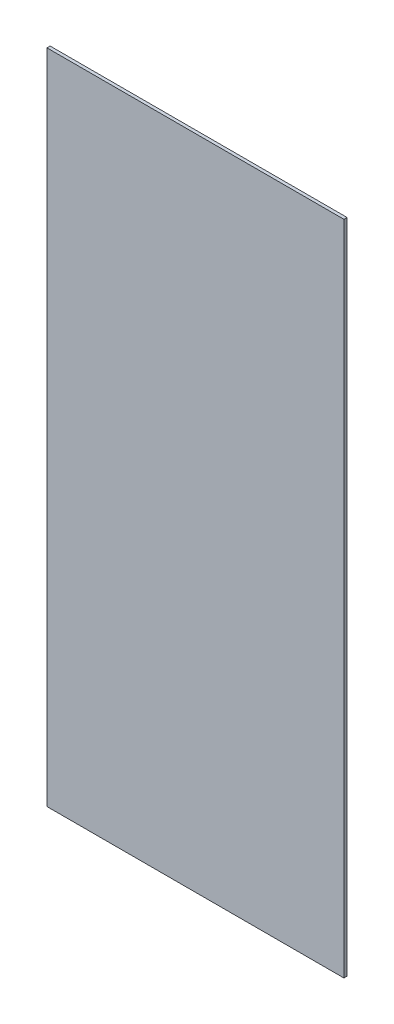
SolidWorks part; units mm, degrees
material "Vidro"
ref_plane "Plano frontal" through (0, 0, 0) normal (0, 0, 1) x (1, 0, 0)
ref_plane "Plano superior" through (0, 0, 0) normal (0, 1, 0) x (1, 0, 0)
ref_plane "Plano direito" through (0, 0, 0) normal (1, 0, 0) x (0, 0, -1)
sketch "Esboço1" plane through (0, 0, 0) normal (0, 0, 1) x (1, 0, 0)
  line L1 (-47, -104) -> (47, -104)
  line L2 (-47, -104) -> (-47, 104)
  line L3 (-47, 104) -> (47, 104)
  line L4 (47, -104) -> (47, 104)
  line L5 (-47, -104) -> (47, 104) construction
  line L6 (-47, 104) -> (47, -104) construction
  point P0 (0, 0)
  dimension "D1" = 94
  dimension "D2" = 208
extrude "Ressalto-extrusão1" add sketch "Esboço1" along normal blind 1
